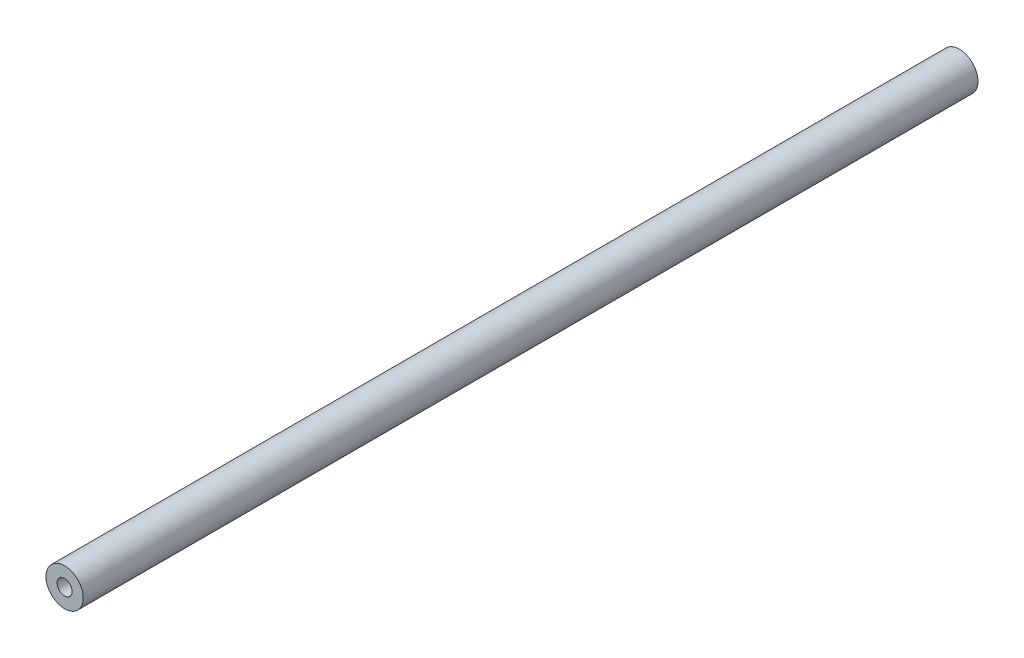
SolidWorks part; units mm, degrees
ref_plane "Front Plane" through (0, 0, 0) normal (0, 0, 1) x (1, 0, 0)
ref_plane "Top Plane" through (0, 0, 0) normal (0, 1, 0) x (1, 0, 0)
ref_plane "Right Plane" through (0, 0, 0) normal (1, 0, 0) x (0, 0, -1)
sketch "Sketch1" plane through (0, 0, 0) normal (0, 0, 1) x (1, 0, 0)
  line L1 (-6.35, 0) -> (6.35, 0) construction
  dimension "OD" = 12.7
sketch "Sketch2" plane through (0, 0, 0) normal (1, 0, 0) x (0, 0, -1)
  line L0 (152.4, 0) -> (-152.4, 0)
  point P0 (-30.48, 0)
  point P3 (30.48, 0)
  point P4 (0, 0)
  dimension "Length" = 304.8
  dimension "D1" = 121.92
  dimension "D2" = 121.92
sketch "Sketch3" plane through (0, 0, 0) normal (0, 0, 1) x (1, 0, 0)
  circle A0 centre (0, 0) radius 6.35
extrude "Boss-Extrude1" add sketch "Sketch3" along normal up to vertex (152.4 mm away) and the other way up to vertex (152.4 mm away) up to point (0, 0, 152.4) other way up to point (0, 0, -152.4)
sketch "Sketch4" plane through (0, 0, -152.4) normal (0, 0, -1) x (-1, 0, 0)
  point P0 (0, 0)
hole_wizard "1/4-20 Tapped Hole1" positions "Sketch5" profile "Sketch7" tap size "1/4-20" standard "ANSI Inch"
sketch "Sketch5" plane through (0, 0, -152.4) normal (0, 0, -1) x (-1, 0, 0)
  point P0 (0, 0)
sketch "Sketch7" plane through (0, 0, -152.4) normal (1, 0, 0) x (0, 1, 0)
  line L0 (0, 0) -> (0, 26.9338)
  line L1 (0, 26.9338) -> (2.5527, 25.4)
  line L2 (2.5527, 25.4) -> (2.5527, 0)
  line L5 (2.5527, 0) -> (0, 0)
  line L10 (0, 26.9338) -> (-2.5527, 25.4) construction
  line L11 (0, -6.35) -> (0, 107.95) construction
  dimension "Tap Drill Dia." = 5.1054
  dimension "Tap Drill Depth" = 25.4
  dimension "Drill Angle" = 118
cosmetic thread "Hole Thread1" parameters "D1"=12.7, "D2"=6.35
mirror "Mirror1" about plane through (0, 0, 0) normal (0, 0, 1) of "1/4-20 Tapped Hole1"
equation "\"D1@Sketch2\"=\"Length@Sketch2\"/2.5"
equation "\"D2@Sketch2\"=\"D1@Sketch2\""
